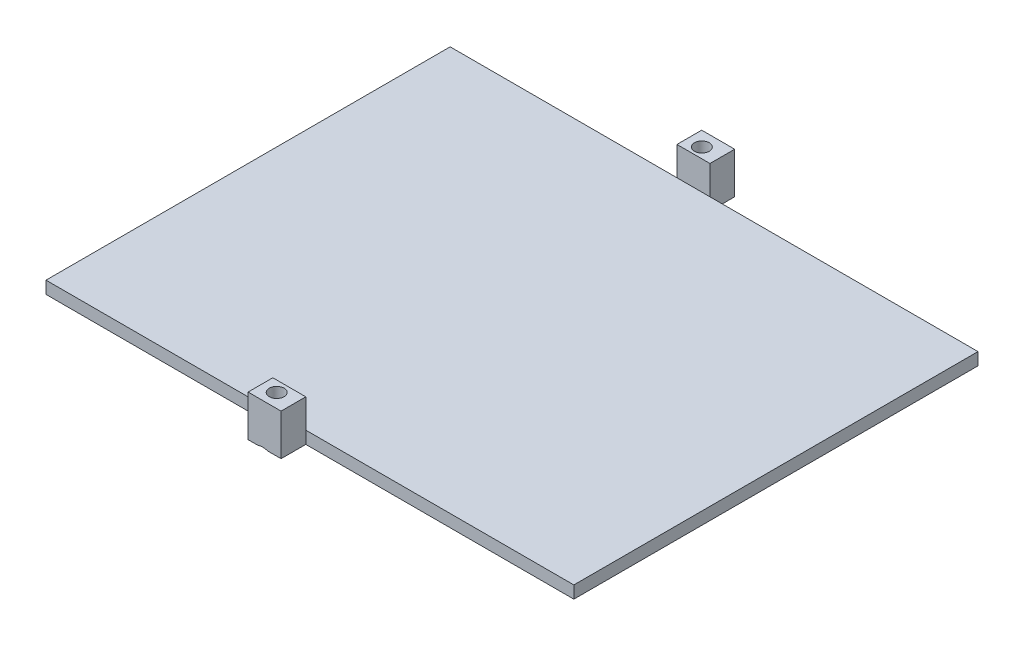
SolidWorks part; units mm, degrees
ref_plane "Front Plane" through (0, 0, 0) normal (0, 0, 1) x (1, 0, 0)
ref_plane "Top Plane" through (0, 0, 0) normal (0, 1, 0) x (1, 0, 0)
ref_plane "Right Plane" through (0, 0, 0) normal (1, 0, 0) x (0, 0, -1)
sketch "Sketch1" plane through (0, 0, 0) normal (0, 1, 0) x (1, 0, 0)
  line L0 (0, 0) -> (64, 0)
  line L1 (64, 0) -> (64, 49)
  line L2 (64, 49) -> (0, 49)
  line L3 (0, 49) -> (0, 0)
extrude "Boss-Extrude1" add sketch "Sketch1" along normal blind 1.5
sketch "Sketch4" plane through (0, 0, 0) normal (0, 1, 0) x (1, 0, 0)
  line L0 (27.5, 0) -> (27.5, -3)
  line L1 (0, 0) -> (64, 0) construction
  line L2 (27.5, -3) -> (31.5, -3)
  line L3 (31.5, -3) -> (31.5, 0)
  line L4 (31.5, 0) -> (27.5, 0)
  line L5 (31.5, 49) -> (31.5, 52)
  line L6 (64, 49) -> (0, 49) construction
  line L7 (31.5, 52) -> (27.5, 52)
  line L8 (27.5, 52) -> (27.5, 49)
  line L9 (27.5, 49) -> (31.5, 49)
extrude "Boss-Extrude2" add sketch "Sketch4" along normal blind 5
hole_wizard "CSK for M1.6 Countersunk Flat Head Screw1" positions "Sketch5" profile "Sketch6" countersink size "M1.6" standard "ISO" end condition through all
sketch "Sketch5" plane through (0, 0, 0) normal (0, -1, 0) x (-1, 0, 0)
  point P0 (-29.279, 50.2373)
  point P2 (-29.279, -1.3062)
sketch "Sketch6" plane through (29.279, 0, -50.2373) normal (1, 0, 0) x (0, 0, -1)
  line L0 (0, 0) -> (0, 5)
  line L1 (0, 5) -> (0.9, 5)
  line L2 (0.9, 5) -> (0.9, 0.9)
  line L3 (0.9, 0.9) -> (1.8, 0)
  line L5 (1.8, 0) -> (0, 0)
  line L6 (-0.9, 0.9) -> (-1.8, 0) construction
  line L11 (0, -6.35) -> (0, 107.95) construction
  dimension "Thru Hole Dia." = 1.8
  dimension "Thru Hole Depth" = 5
  dimension "Near C'Sink Dia." = 3.6
  dimension "Near C'Sink Angle" = 90
